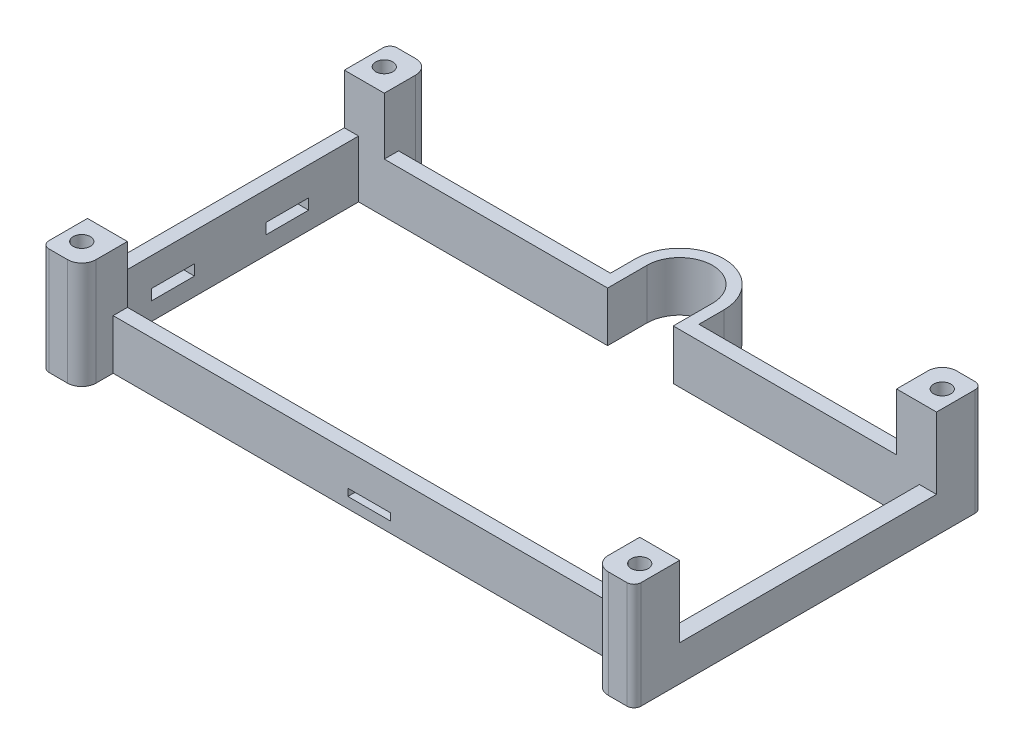
SolidWorks part; units mm, degrees
material "ABS PC"
ref_plane "Front Plane" through (0, 0, 0) normal (0, 0, 1) x (1, 0, 0)
ref_plane "Top Plane" through (0, 0, 0) normal (0, 1, 0) x (1, 0, 0)
ref_plane "Right Plane" through (0, 0, 0) normal (1, 0, 0) x (0, 0, -1)
sketch "Sketch1" plane through (0, 0, 0) normal (0, 1, 0) x (1, 0, 0)
  line L0 (2.4, -23.4) -> (2.4, 23.4)
  line L6 (0, 18) -> (0, -18)
  line L7 (0, -18) -> (-15, -18)
  line L8 (-15, -18) -> (-15, -20)
  line L9 (-15, -20) -> (-3.2, -20)
  line L10 (-3.2, -20) -> (-3.2, -22.4)
  line L11 (-1.2, -24.4) -> (1.4, -24.4)
  line L12 (0, 0) -> (8.7, 0) construction
  line L13 (-1.2, 24.4) -> (1.4, 24.4)
  line L14 (-3.2, 20) -> (-3.2, 22.4)
  line L15 (-15, 20) -> (-3.2, 20)
  line L16 (-15, 18) -> (-15, 20)
  line L17 (0, 18) -> (-15, 18)
  arc A2 (-3.2, -22.4) -> (-1.2, -24.4) centre (-1.2, -22.4) ccw
  arc A3 (1.4, -24.4) -> (2.4, -23.4) centre (1.4, -23.4) ccw
  arc A4 (1.4, 24.4) -> (2.4, 23.4) centre (1.4, 23.4) cw
  arc A5 (-3.2, 22.4) -> (-1.2, 24.4) centre (-1.2, 22.4) cw
  circle A6 centre (0, -21.2) radius 1.2
  circle A7 centre (0, 21.2) radius 1.2
  point P22 (2.4, 0)
  point P29 (0, 0)
  dimension "D7" = 2
  dimension "D8" = 1
  dimension "D14" = 2.4
  dimension "D1" = 24.4
  dimension "D2" = 2.4
  dimension "D3" = 2
  dimension "D4" = 18
  dimension "D5" = 15
  dimension "D6" = 5.6
  dimension "D9" = 1
  dimension "D10" = 2.6
  dimension "D11" = 1
  dimension "D12" = 2
  dimension "D13" = 2
  dimension "D15" = 3.2
  dimension "D16" = 2.4
extrude "Boss-Extrude1" add sketch "Sketch1" along normal blind 15
sketch "Sketch3" plane through (0, 0, 0) normal (0, 1, 0) x (1, 0, 0)
  line L0 (-15, -18) -> (-15, 18)
  line L12 (-1.2, -24.4) -> (1.4, -24.4)
  line L13 (-3.2, -20) -> (-3.2, -22.4)
  line L14 (-15, -20) -> (-3.2, -20)
  line L15 (-15, -18) -> (-15, -20)
  line L16 (0, -18) -> (-15, -18)
  line L17 (0, 18) -> (0, -18)
  line L18 (-15, 18) -> (0, 18)
  line L19 (-15, 20) -> (-15, 18)
  line L20 (-3.2, 20) -> (-15, 20)
  line L21 (-3.2, 22.4) -> (-3.2, 20)
  line L22 (1.4, 24.4) -> (-1.2, 24.4)
  line L23 (2.4, -23.4) -> (2.4, 23.4)
  line L24 (-1.2, -24.4) -> (1.4, -24.4) construction
  line L25 (-3.2, -20) -> (-3.2, -22.4) construction
  line L26 (-15, -20) -> (-3.2, -20) construction
  line L27 (-15, -18) -> (-15, -20) construction
  line L28 (0, -18) -> (-15, -18)
  line L29 (0, 18) -> (0, -18)
  line L30 (-15, 18) -> (0, 18)
  line L31 (-15, 20) -> (-15, 18) construction
  line L32 (-3.2, 20) -> (-15, 20) construction
  line L33 (-3.2, 22.4) -> (-3.2, 20) construction
  line L34 (1.4, 24.4) -> (-1.2, 24.4) construction
  line L35 (2.4, -23.4) -> (2.4, 23.4) construction
  arc A4 (1.4, -24.4) -> (2.4, -23.4) centre (1.4, -23.4) ccw
  arc A5 (-3.2, -22.4) -> (-1.2, -24.4) centre (-1.2, -22.4) ccw
  arc A6 (-1.2, 24.4) -> (-3.2, 22.4) centre (-1.2, 22.4) ccw
  arc A7 (2.4, 23.4) -> (1.4, 24.4) centre (1.4, 23.4) ccw
  arc A8 (1.4, -24.4) -> (2.4, -23.4) centre (1.4, -23.4) ccw construction
  arc A9 (-3.2, -22.4) -> (-1.2, -24.4) centre (-1.2, -22.4) ccw construction
  arc A10 (-1.2, 24.4) -> (-3.2, 22.4) centre (-1.2, 22.4) ccw construction
  arc A11 (2.4, 23.4) -> (1.4, 24.4) centre (1.4, 23.4) ccw construction
  dimension "D1" = 0
extrude "Boss-Extrude3" add sketch "Sketch3" along normal blind 1.5
sketch "Sketch4" plane through (-15, 0, 0) normal (-1, 0, 0) x (0, 0, 1)
  line L0 (-18, 1.5) -> (-18, 0)
  line L8 (-20, 0) -> (20, 0)
  line L9 (20, 0) -> (20, 15)
  line L10 (20, 15) -> (18, 15)
  line L11 (18, 15) -> (18, 1.5)
  line L12 (18, 1.5) -> (-18, 1.5)
  line L13 (-18, 1.5) -> (-18, 15)
  line L14 (-18, 15) -> (-20, 15)
  line L15 (-20, 15) -> (-20, 0)
  line L16 (-20, 0) -> (-18, 0)
  line L21 (-18, 1.5) -> (-18, 15)
  line L22 (-18, 15) -> (-20, 15)
  line L23 (-20, 15) -> (-20, 0)
  dimension "D1" = 0
extrude "Boss-Extrude4" add sketch "Sketch4" along normal blind 19.5
sketch "Sketch6" plane through (0, 15, 0) normal (0, 1, 0) x (1, 0, 0)
  line L0 (-49.4072, 20) -> (-29.2339, 20) construction
  line L1 (-45.3, 20) -> (-45.3, 23.5)
  line L2 (-3.2, 20) -> (-34.5, 20) construction
  line L3 (-43.7, 20) -> (-43.7, 23.5)
  line L4 (-43.7, 23.5) -> (-34.5, 23.5) construction
  line L5 (-34.5, 23.5) -> (-34.5, 20)
  line L6 (-32.9, 23.5) -> (-32.9, 20)
  line L7 (-43.7, 18) -> (-80.6, 18)
  line L8 (-80.6, 18) -> (-80.6, 23.4)
  line L9 (-79.6, 24.4) -> (-77, 24.4)
  line L10 (-75, 22.4) -> (-75, 20)
  line L11 (-75, 20) -> (-45.3, 20)
  line L12 (-43.7, 20) -> (-43.7, 18)
  line L13 (-34.5, 20) -> (-32.9, 20)
  line L14 (0, 0) -> (-50000, 0) construction
  line L15 (-80.6, -18) -> (-15, -18)
  line L16 (-75, -20) -> (-15, -20)
  line L17 (-75, -22.4) -> (-75, -20)
  line L18 (-79.6, -24.4) -> (-77, -24.4)
  line L19 (-80.6, -18) -> (-80.6, -23.4)
  line L20 (0, -18) -> (-15, -18) construction
  line L21 (-15, -18) -> (-15, -20) construction
  line L22 (-15, -18) -> (-15, -20)
  arc A0 (-43.7, 23.5) -> (-34.5, 23.5) centre (-39.1, 23.5) cw
  arc A1 (-80.6, 23.4) -> (-79.6, 24.4) centre (-79.6, 23.4) cw
  arc A2 (-77, 24.4) -> (-75, 22.4) centre (-77, 22.4) cw
  arc A3 (-45.3, 23.5) -> (-32.9, 23.5) centre (-39.1, 23.5) cw
  circle A4 centre (-78.2, 21.2) radius 1.2
  circle A5 centre (-78.2, -21.2) radius 1.2
  arc A6 (-77, -24.4) -> (-75, -22.4) centre (-77, -22.4) ccw
  arc A7 (-80.6, -23.4) -> (-79.6, -24.4) centre (-79.6, -23.4) ccw
  dimension "D5" = 1
  dimension "D6" = 2
  dimension "D7" = 2.4
  dimension "D1" = 9.2
  dimension "D2" = 3.5
  dimension "D4" = 2
  dimension "D8" = 2.4
  dimension "D9" = 3.2
  dimension "D10" = 2.6
  dimension "D11" = 36.9
  dimension "D3" = 1.6
extrude "Boss-Extrude5" add sketch "Sketch6" against normal blind 15
sketch "Sketch7" plane through (0, 0, 0) normal (0, -1, 0) x (1, 0, 0)
  line L0 (-80.6, -18) -> (-43.7, -18) construction
  line L1 (-80.6, 18) -> (-78.6, 18)
  line L2 (-80.6, 18) -> (-80.6, -18)
  line L3 (-80.6, -18) -> (-78.6, -18)
  line L4 (-78.6, 18) -> (-78.6, -18)
  dimension "D1" = 2
extrude "Boss-Extrude6" add sketch "Sketch7" against normal blind 8
sketch "Sketch8" plane through (0, 0, 18) normal (0, 0, -1) x (-1, 0, 0)
  line L0 (75, 0) -> (3.2, 0) construction
  line L1 (42.1, 1.5) -> (36.1, 1.5)
  line L2 (42.1, 1.5) -> (42.1, 2.5)
  line L3 (42.1, 2.5) -> (36.1, 2.5)
  line L4 (36.1, 1.5) -> (36.1, 2.5)
  line L5 (75, 0) -> (3.2, 0) construction
  line L6 (39.1, 0) -> (39.1, 50000) construction
  point P8 (39.1, 0)
  point P9 (39.1, 1.5)
  dimension "D1" = 6
  dimension "D2" = 1
  dimension "D3" = 1.5
extrude "Cut-Extrude1" cut sketch "Sketch8" against normal blind 5
sketch "Sketch9" plane through (-78.6, 0, 0) normal (1, 0, 0) x (0, 0, -1)
  line L0 (0, 0) -> (0, 50000) construction
  line L1 (11, 2.5) -> (5, 2.5)
  line L2 (11, 2.5) -> (11, 4)
  line L3 (11, 4) -> (5, 4)
  line L4 (5, 2.5) -> (5, 4)
  line L9 (18, 0) -> (-18, 0) construction
  line L10 (18, 8) -> (-18, 8) construction
  line L11 (-5, 2.5) -> (-5, 4)
  line L12 (-11, 4) -> (-5, 4)
  line L13 (-11, 2.5) -> (-11, 4)
  line L14 (-11, 2.5) -> (-5, 2.5)
  point P8 (0, 0)
  point P11 (0, 8)
  dimension "D1" = 5
  dimension "D2" = 6
  dimension "D3" = 1.5
  dimension "D4" = 2.5
extrude "Cut-Extrude2" cut sketch "Sketch9" against normal blind 5
sketch "Sketch10" plane through (0, 0, -20) normal (0, 0, -1) x (-1, 0, 0)
  line L0 (75, 0) -> (75, 15) construction
  line L1 (75, 7) -> (3.2, 7)
  line L2 (75, 7) -> (75, 15)
  line L3 (75, 15) -> (3.2, 15)
  line L4 (3.2, 7) -> (3.2, 15)
  dimension "D1" = 8
extrude "Cut-Extrude3" cut sketch "Sketch10" against normal through all and the other way through all
sketch "Sketch11" plane through (2.4, 0, 0) normal (1, 0, 0) x (0, 0, -1)
  line L0 (18, 0) -> (-18, 0) construction
  line L1 (18, 0) -> (-18, 0) construction
  line L2 (18, 5) -> (18, 15)
  line L3 (-23.4, 15) -> (23.4, 15) construction
  line L4 (18, 15) -> (-18, 15)
  line L5 (-18, 15) -> (-18, 5)
  line L6 (-18, 5) -> (18, 5)
  dimension "D1" = 10
extrude "Cut-Extrude4" cut sketch "Sketch11" against normal blind 10
sketch "Sketch12" plane through (0, 0, 0) normal (0, -1, 0) x (1, 0, 0)
  line L0 (0, 18) -> (0, -18) construction
  line L1 (0, 18) -> (0, -18)
  line L2 (0, -18) -> (-15, -18)
  line L3 (-15, -18) -> (-15, 18)
  line L4 (-15, 18) -> (0, 18)
extrude "Cut-Extrude5" cut sketch "Sketch12" against normal blind 10
equation "\"ˇ5\"=10.0979"
